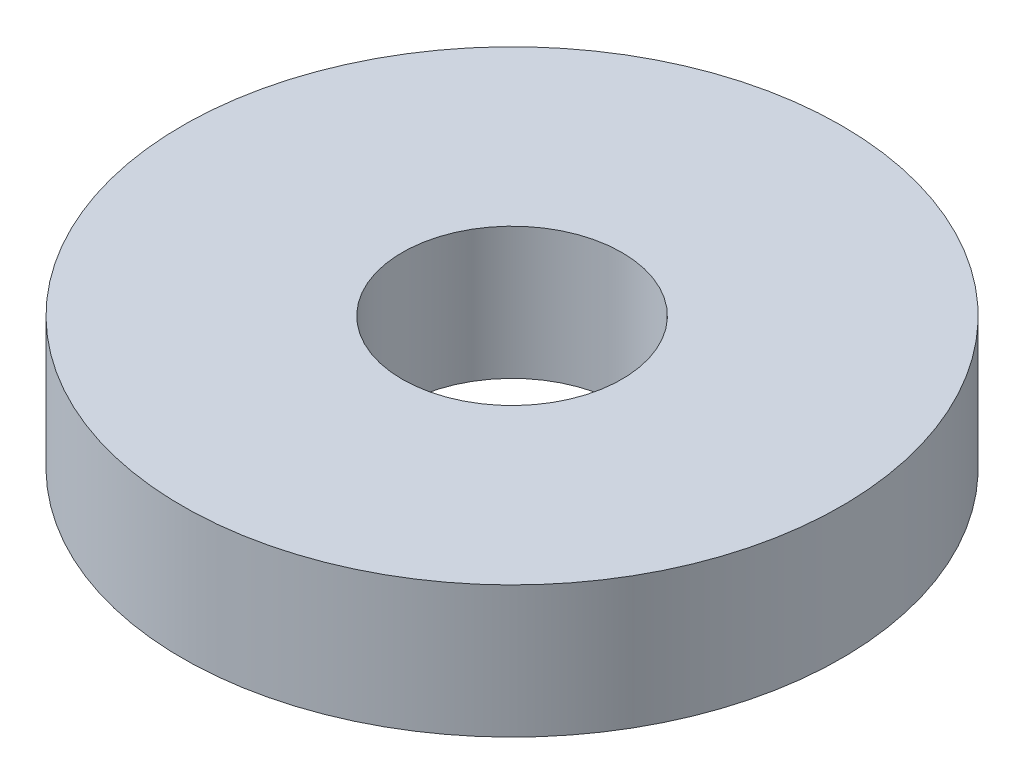
SolidWorks part; units mm, degrees
ref_plane "Front Plane" through (0, 0, 0) normal (0, 0, 1) x (1, 0, 0)
ref_plane "Top Plane" through (0, 0, 0) normal (0, 1, 0) x (1, 0, 0)
ref_plane "Right Plane" through (0, 0, 0) normal (1, 0, 0) x (0, 0, -1)
sketch "Sketch1" plane through (0, 0, 0) normal (0, 0, 1) x (1, 0, 0)
  line L0 (0, 0) -> (0, 34.7748) construction
  line L2 (-5, 3.0672) -> (-15, 3.0672)
  line L3 (-5, 3.0672) -> (-5, -2.9328)
  line L4 (-5, -2.9328) -> (-15, -2.9328)
  line L5 (-15, 3.0672) -> (-15, -2.9328)
  dimension "D1" = 30
  dimension "D2" = 10
  dimension "D3" = 6
revolve "Revolve1" add sketch "Sketch1" angle 360 about L0
